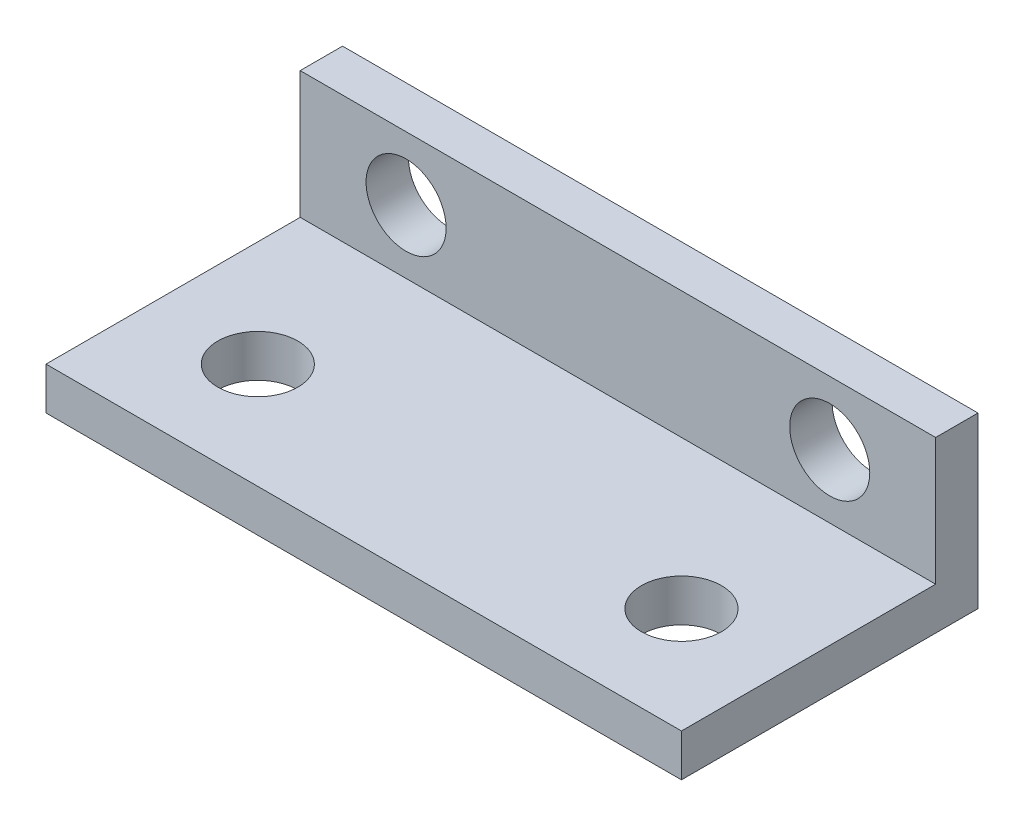
SolidWorks part; units mm, degrees
ref_plane "Front Plane" through (0, 0, 0) normal (0, 0, 1) x (1, 0, 0)
ref_plane "Top Plane" through (0, 0, 0) normal (0, 1, 0) x (1, 0, 0)
ref_plane "Right Plane" through (0, 0, 0) normal (1, 0, 0) x (0, 0, -1)
sketch "Sketch2" plane through (0, 0, 0) normal (1, 0, 0) x (0, 0, -1)
  line L1 (0, 0) -> (10.16, 0)
  line L2 (0, 0) -> (0, 10.16)
  line L3 (0, 10.16) -> (10.16, 10.16)
  line L4 (10.16, 0) -> (10.16, 10.16)
  line L5 (5.08, 10.16) -> (5.08, 0) construction
  line L6 (0, 5.08) -> (10.16, 5.08) construction
  point P204 (5.08, 5.08)
  dimension "D1" = 10.16
extrude "Boss-Extrude1" add sketch "Sketch2" along normal blind 38.1
sketch "Sketch3" plane through (38.1, 0, 0) normal (1, 0, 0) x (0, 0, -1)
  line L0 (10.16, 0) -> (10.16, 10.16) construction
  line L1 (0, 10.16) -> (7.62, 10.16)
  line L2 (0, 10.16) -> (0, 2.54)
  line L3 (0, 2.54) -> (7.62, 2.54)
  line L4 (7.62, 10.16) -> (7.62, 2.54)
  line L5 (3.81, 2.54) -> (3.81, 10.16) construction
  line L6 (0, 6.35) -> (7.62, 6.35) construction
  point P556 (3.81, 6.35)
  dimension "D1" = 2.54
extrude "Cut-Extrude1" cut sketch "Sketch3" against normal up to surface (38.1 mm away) and the other way through all up to face at (0, 5.08, -5.08)
sketch "Sketch7" plane through (0, 0, -7.62) normal (0, 0, 1) x (1, 0, 0)
  line L0 (0, 6.35) -> (38.1, 6.35) construction
  line L1 (0, 2.54) -> (0, 10.16) construction
  line L2 (38.1, 10.16) -> (38.1, 2.54) construction
  line L3 (38.1, 0) -> (0, 0) construction
  line L4 (6.35, 10.16) -> (6.35, 2.54) construction
  line L5 (0, 10.16) -> (38.1, 10.16) construction
  line L6 (0, 2.54) -> (38.1, 2.54) construction
  line L7 (19.05, 10.16) -> (19.05, 2.54) construction
  line L8 (31.75, 10.16) -> (31.75, 2.54) construction
  dimension "D1" = 6.35
  dimension "D2" = 6.35
hole_wizard "M4 Clearance Hole2" positions "Sketch10" profile "Sketch11" hole size "M4" standard "ANSI Metric" end condition through all
sketch "Sketch10" plane through (0, 0, -7.62) normal (0, 0, 1) x (1, 0, 0)
  line L0 (6.35, 10.16) -> (6.35, 2.54) construction
  line L1 (31.75, 10.16) -> (31.75, 2.54) construction
  point P0 (6.35, 6.35)
  point P4 (31.75, 6.35)
sketch "Sketch11" plane through (6.35, 6.35, -7.62) normal (1, 0, 0) x (0, -1, 0)
  line L0 (0, 0) -> (0, 2.54)
  line L1 (0, 2.54) -> (2.4, 2.54)
  line L2 (2.4, 2.54) -> (2.4, 0)
  line L5 (2.4, 0) -> (0, 0)
  line L11 (0, -6.35) -> (0, 107.95) construction
  dimension "Thru Hole Dia." = 4.8
  dimension "Thru Hole Depth" = 2.54
sketch "Sketch13" plane through (0, 0, 0) normal (0, 0, 1) x (1, 0, 0)
  line L1 (0, 2.54) -> (38.1, 2.54)
  line L2 (0, 2.54) -> (0, 0)
  line L3 (0, 0) -> (38.1, 0)
  line L4 (38.1, 2.54) -> (38.1, 0)
  line L5 (19.05, 0) -> (19.05, 2.54) construction
  line L6 (0, 1.27) -> (38.1, 1.27) construction
  point P300 (19.05, 1.27)
extrude "Boss-Extrude2" add sketch "Sketch13" along normal blind 7.62
sketch "Sketch14" plane through (0, 2.54, 0) normal (0, 1, 0) x (1, 0, 0)
  line L0 (0, -1.27) -> (38.1, -1.27) construction
  line L1 (0, 7.62) -> (38.1, 7.62) construction
  line L3 (0, -7.62) -> (0, 7.62) construction
  line L4 (38.1, 7.62) -> (38.1, -7.62) construction
  line L5 (38.1, -7.62) -> (0, -7.62) construction
  line L6 (6.35, 7.62) -> (6.35, -7.62) construction
  line L7 (31.75, 7.62) -> (31.75, -7.62) construction
  dimension "D1" = 6.35
hole_wizard "M4 Clearance Hole3" positions "Sketch15" profile "Sketch16" hole size "M4" standard "ANSI Metric" end condition through all
sketch "Sketch15" plane through (0, 2.54, 0) normal (0, 1, 0) x (1, 0, 0)
  line L0 (0, -1.27) -> (38.1, -1.27) construction
  line L1 (6.35, 7.62) -> (6.35, -7.62) construction
  line L2 (31.75, 7.62) -> (31.75, -7.62) construction
  point P0 (6.35, -1.27)
  point P6 (31.75, -1.27)
sketch "Sketch16" plane through (6.35, 2.54, 1.27) normal (1, 0, 0) x (0, 0, 1)
  line L0 (0, 0) -> (0, 2.54)
  line L1 (0, 2.54) -> (2.4, 2.54)
  line L2 (2.4, 2.54) -> (2.4, 0)
  line L5 (2.4, 0) -> (0, 0)
  line L11 (0, -6.35) -> (0, 107.95) construction
  dimension "Thru Hole Dia." = 4.8
  dimension "Thru Hole Depth" = 2.54
sketch "Sketch17" [suppressed] plane through (0, 0, -10.16) normal (0, 0, -1) x (-1, 0, 0)
  line L0 (-38.1, 0) -> (0, 0) construction
  line L1 (-38.1, 10.16) -> (-12.7, 10.16)
  line L2 (-38.1, 10.16) -> (-38.1, 0)
  line L3 (-38.1, 0) -> (-12.7, 0)
  line L4 (-12.7, 10.16) -> (-12.7, 0)
  line L5 (-25.4, 0) -> (-25.4, 10.16) construction
  line L6 (-38.1, 5.08) -> (-12.7, 5.08) construction
  circle A0 centre (-6.35, 6.35) radius 2.4 construction
  point P236 (-25.4, 5.08)
  dimension "D1" = 6.35
extrude "Cut-Extrude2" [suppressed] cut sketch "Sketch17" against normal up to surface (17.78 mm away)
